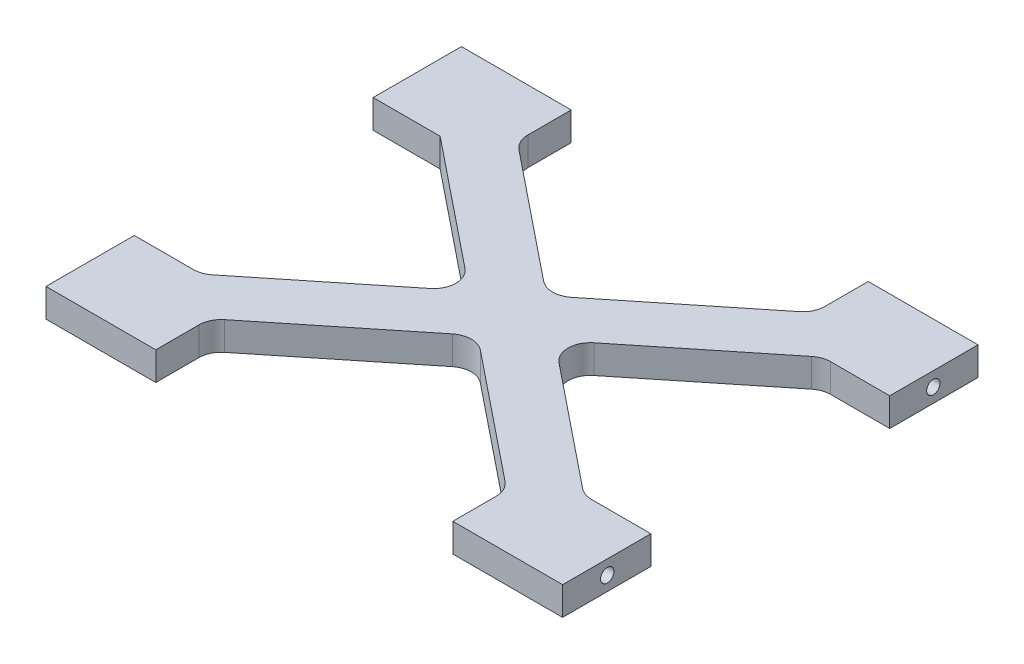
SolidWorks part; units mm, degrees
material "1060 Alloy"
ref_plane "Front Plane" through (0, 0, 0) normal (0, 0, 1) x (1, 0, 0)
ref_plane "Top Plane" through (0, 0, 0) normal (0, 1, 0) x (1, 0, 0)
ref_plane "Right Plane" through (0, 0, 0) normal (1, 0, 0) x (0, 0, -1)
sketch "Sketch1" plane through (0, 0, 0) normal (0, 1, 0) x (1, 0, 0)
  line L1 (57.825, 46.5) -> (-57.825, 46.5) construction
  line L2 (57.825, 46.5) -> (57.825, -46.5) construction
  line L3 (57.825, -46.5) -> (-57.825, -46.5) construction
  line L4 (-57.825, 46.5) -> (-57.825, -46.5) construction
  line L5 (-57.825, 46.5) -> (57.825, -46.5) construction
  line L6 (-57.825, 26.7384) -> (-42.825, 26.7384)
  line L36 (-42.825, 26.7384) -> (-9.5745, 0)
  line L37 (-9.5745, 0) -> (-42.825, -26.7384)
  line L38 (-42.825, -26.7384) -> (-57.825, -26.7384)
  line L39 (-57.825, -26.7384) -> (-57.825, -46.5)
  line L40 (-57.825, -46.5) -> (-33.2505, -46.5)
  line L41 (-33.2505, -46.5) -> (-33.2505, -34.4377)
  line L42 (-33.2505, -34.4377) -> (0, -7.6993)
  line L43 (0, -7.6993) -> (33.2505, -34.4377)
  line L44 (33.2505, -34.4377) -> (33.2505, -46.5)
  line L45 (33.2505, -46.5) -> (57.825, -46.5)
  line L46 (57.825, -46.5) -> (57.825, -26.7384)
  line L47 (57.825, -26.7384) -> (42.825, -26.7384)
  line L48 (42.825, -26.7384) -> (9.5745, 0)
  line L49 (9.5745, 0) -> (42.825, 26.7384)
  line L50 (42.825, 26.7384) -> (57.825, 26.7384)
  line L51 (57.825, 26.7384) -> (57.825, 46.5)
  line L52 (57.825, 46.5) -> (33.2505, 46.5)
  line L53 (33.2505, 46.5) -> (33.2505, 34.4377)
  line L54 (33.2505, 34.4377) -> (0, 7.6993)
  line L55 (0, 7.6993) -> (-33.2505, 34.4377)
  line L56 (-33.2505, 34.4377) -> (-33.2505, 46.5)
  line L57 (-33.2505, 46.5) -> (-57.825, 46.5)
  line L58 (-57.825, 46.5) -> (-57.825, 26.7384)
  line L59 (-57.825, -46.5) -> (57.825, 46.5) construction
  line L65 (42.825, 26.7384) -> (33.2505, 34.4377) construction
  dimension "D1" = 115.65
  dimension "D2" = 93
  dimension "D3" = 12
  dimension "D4" = 15
extrude "Boss-Extrude1" add sketch "Sketch1" along normal blind 6.35
fillet "Fillet1" radius 5 11 edges at (-33.2505, 3.175, -34.4377) (33.2505, 3.175, -34.4377) (42.825, 3.175, -26.7384) (42.825, 3.175, 26.7384) (33.2505, 3.175, 34.4377) (-33.2505, 3.175, 34.4377) (-42.825, 3.175, 26.7384) (-9.5745, 3.175, 0) (0, 3.175, -7.6993) (9.5745, 3.175, 0) (0, 3.175, 7.6993)
sketch "Sketch2" plane through (57.825, 0, 0) normal (1, 0, 0) x (0, 0, -1)
  line L0 (46.5, 6.35) -> (46.5, 0) construction
  line L1 (0, 0) -> (0, 6.35) construction
  line L2 (3.8964, 6.35) -> (-3.8964, 6.35) construction
  circle A0 centre (36.5, 3.175) radius 1.5
  circle A1 centre (-36.5, 3.175) radius 1.5
  point P7 (46.5, 3.175)
  dimension "D1" = 3
  dimension "D2" = 10
extrude "Cut-Extrude1" cut sketch "Sketch2" against normal blind 20
mirror "Mirror1" about plane through (0, 0, 0) normal (1, 0, 0) of "Cut-Extrude1"
equation "\"L1L\"=500"
equation "\"L1Thick\"=6.35"
equation "\"Harm-Drive-Outer\"=74.5"
equation "\"L1-Spacing\"=115.65"
equation "\"L-Bracket-HoleToWall\"=12.5"
equation "\"L-Bracket-HoleToSide\"=11"
equation "\"Bracket-Hole-D\"=6.8"
equation "\"D1@Sketch1\"=\"L1-Spacing\""
